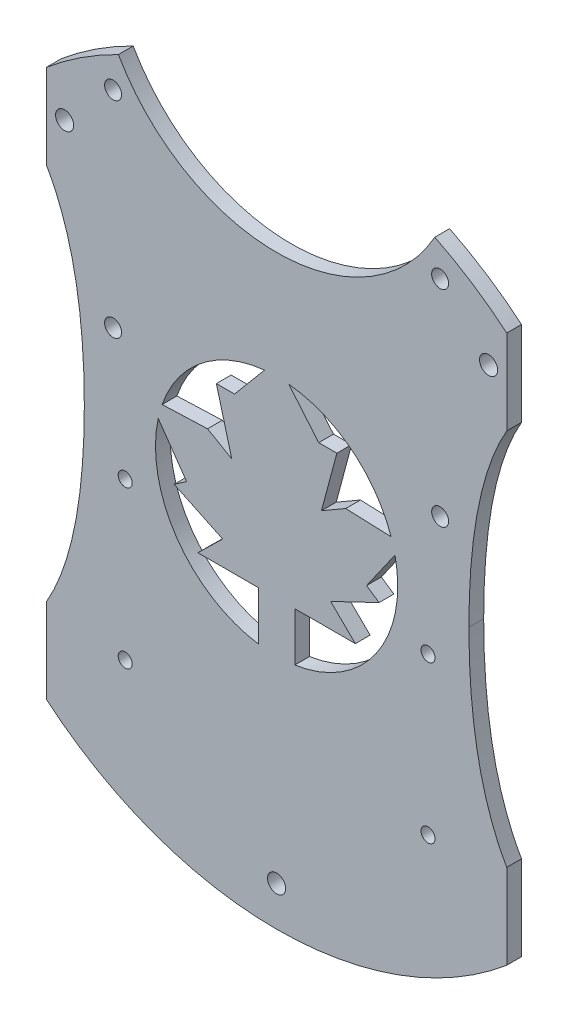
SolidWorks part; units mm, degrees
ref_plane "Front Plane" through (0, 0, 0) normal (0, 0, 1) x (1, 0, 0)
ref_plane "Top Plane" through (0, 0, 0) normal (0, 1, 0) x (1, 0, 0)
ref_plane "Right Plane" through (0, 0, 0) normal (1, 0, 0) x (0, 0, -1)
sketch "Sketch1" plane through (0, 0, 0) normal (0, 0, 1) x (1, 0, 0)
  line L0 (0, 47.9049) -> (0, -75) construction
  line L1 (-48.26, 57.4106) -> (-48.26, -57.4106)
  line L2 (48.26, 57.4106) -> (48.26, -57.4106)
  arc A0 (-33.1727, 67.265) -> (-48.26, 57.4106) centre (0, 0) ccw
  arc A1 (-33.1727, 67.265) -> (33.1727, 67.265) centre (0, 86.0049) ccw
  circle A2 centre (0, -66.675) radius 1.8987
  circle A3 centre (-44.45, 49.6966) radius 1.8987
  circle A4 centre (44.45, 49.6966) radius 1.8986
  arc A5 (-48.26, -57.4106) -> (48.26, -57.4106) centre (0, 0) ccw
  arc A6 (48.26, 57.4106) -> (33.1727, 67.265) centre (0, 0) ccw
  circle A7 centre (0, 0) radius 66.675 construction
  dimension "D8" = 3.7973
  dimension "D11" = 3.7973
  dimension "D5" = 150
  dimension "D7" = 133.35
  dimension "D2" = 66.3453
  dimension "D3" = 38.1
  dimension "D4" = 44.45
  dimension "D6" = 48.26
extrude "Boss-Extrude3" add sketch "Sketch1" along normal blind 3.0988
sketch "Sketch2" plane through (0, 0, 3.0988) normal (0, 0, 1) x (1, 0, 0)
  line L0 (0, 47.9049) -> (0, -75) construction
  line L1 (-34.925, -41.98) -> (34.925, -41.98) construction
  line L2 (-34.925, -61.03) -> (-34.925, -22.93) construction
  line L3 (-34.925, -61.03) -> (34.925, -61.03) construction
  line L4 (34.925, -61.03) -> (34.925, -22.93) construction
  line L5 (-34.925, -22.93) -> (34.925, -22.93) construction
  line L6 (0, -61.03) -> (0, -22.93) construction
  line L7 (-28.575, -55.7849) -> (-28.575, -28.1751) construction
  line L8 (-28.575, -55.7849) -> (28.575, -55.7849) construction
  line L9 (28.575, -55.7849) -> (28.575, -28.1751) construction
  line L10 (-28.575, -28.1751) -> (28.575, -28.1751) construction
  line L11 (-28.575, -55.7849) -> (28.575, -28.1751) construction
  line L12 (28.575, -55.7849) -> (-28.575, -28.1751) construction
  line L13 (-34.925, -9.1251) -> (34.925, -9.1251) construction
  line L14 (34.925, 9.9249) -> (34.925, -22.93) construction
  line L15 (-34.925, -22.93) -> (34.925, -22.93) construction
  line L16 (-34.925, 9.9249) -> (-34.925, -22.93) construction
  line L17 (-34.925, 9.9249) -> (34.925, 9.9249) construction
  line L18 (0, -22.93) -> (0, 9.9249) construction
  line L19 (-28.575, -22.93) -> (-28.575, 4.6798) construction
  line L20 (-28.575, -22.93) -> (28.575, -22.93) construction
  line L21 (28.575, -22.93) -> (28.575, 4.6798) construction
  line L22 (-28.575, 4.6798) -> (28.575, 4.6798) construction
  line L23 (-28.575, -22.93) -> (28.575, 4.6798) construction
  line L24 (28.575, -22.93) -> (-28.575, 4.6798) construction
  arc A0 (-33.1727, 67.265) -> (33.1727, 67.265) centre (0, 86.0049) ccw construction
  arc A1 (-48.26, -57.4106) -> (48.26, -57.4106) centre (0, 0) ccw construction
  circle A2 centre (-31.75, -41.98) radius 1.4732
  circle A3 centre (31.75, -41.98) radius 1.4732
  circle A4 centre (-31.75, -9.1251) radius 1.4732
  circle A5 centre (31.75, -9.1251) radius 1.4732
  point P8 (0, -41.98)
  point P25 (0, -9.1251)
  dimension "D7" = 2.9464
  dimension "D11" = 2.9464
  dimension "D1" = 57.15
  dimension "D2" = 27.6098
  dimension "D3" = 3.175
  dimension "D4" = 33.02
  dimension "D5" = 38.1
  dimension "D6" = 69.85
  dimension "D8" = 57.15
  dimension "D9" = 27.6098
  dimension "D10" = 32.8549
  dimension "D12" = 32.8549
  dimension "D13" = 69.85
  dimension "D14" = 28.575
extrude "Cut-Extrude1" cut sketch "Sketch2" against normal up to surface (3.0988 mm away) up to face at (1.8987, -66.675, 0)
sketch "Sketch3" plane through (0, 0, 3.0988) normal (0, 0, 1) x (1, 0, 0)
  line L0 (0, 47.9049) -> (0, -75) construction
  line L1 (0, 25.4) -> (0, -25.4) construction
  line L2 (8.8271, 17.78) -> (2.54, 25.2727)
  line L3 (8.8271, 17.78) -> (12.6371, 17.78)
  line L4 (12.6371, 17.78) -> (9.4043, 5.715)
  line L5 (9.4043, 5.715) -> (14.4843, 8.6479)
  line L6 (14.4843, 8.6479) -> (24.0093, 8.2894)
  line L7 (18.8681, -3.1406) -> (24.8262, 5.3684)
  line L8 (18.8681, -3.1406) -> (21.4871, -4.9356)
  line L9 (21.4871, -4.9356) -> (11.3271, -9.7979)
  line L10 (11.3271, -9.7979) -> (16.51, -14.8779)
  line L11 (16.51, -14.8779) -> (3.81, -14.8779)
  line L12 (3.81, -14.8779) -> (3.81, -25.1126)
  line L13 (-3.81, -14.8779) -> (-3.81, -25.1126)
  line L14 (-16.51, -14.8779) -> (-3.81, -14.8779)
  line L15 (-11.3271, -9.7979) -> (-16.51, -14.8779)
  line L16 (-21.4871, -4.9356) -> (-11.3271, -9.7979)
  line L17 (-18.8681, -3.1406) -> (-21.4871, -4.9356)
  line L18 (-18.8681, -3.1406) -> (-24.8262, 5.3684)
  line L19 (-14.4843, 8.6479) -> (-24.0093, 8.2894)
  line L20 (-9.4043, 5.715) -> (-14.4843, 8.6479)
  line L21 (-12.6371, 17.78) -> (-9.4043, 5.715)
  line L22 (-8.8271, 17.78) -> (-12.6371, 17.78)
  line L23 (-8.8271, 17.78) -> (-2.54, 25.2727)
  arc A0 (-33.1727, 67.265) -> (33.1727, 67.265) centre (0, 86.0049) ccw construction
  arc A1 (-48.26, -57.4106) -> (48.26, -57.4106) centre (0, 0) ccw construction
  arc A2 (3.81, -25.1126) -> (24.8262, 5.3684) centre (0, 0) ccw
  arc A3 (-24.8262, 5.3684) -> (-3.81, -25.1126) centre (0, 0) ccw
  arc A4 (-2.54, 25.2727) -> (-24.0093, 8.2894) centre (0, 0) ccw
  arc A5 (24.0093, 8.2894) -> (2.54, 25.2727) centre (0, 0) ccw
  circle A6 centre (0, 0) radius 25.4 construction
  dimension "D1" = 7.62
  dimension "D2" = 3.81
  dimension "D3" = 12.065
  dimension "D4" = 75
  dimension "D5" = 5.08
  dimension "D6" = 45
  dimension "D7" = 9.525
  dimension "D8" = 3.175
  dimension "D9" = 10.16
  dimension "D10" = 60
  dimension "D11" = 5.08
  dimension "D12" = 12.7
  dimension "D13" = 70
  dimension "D14" = 3.81
  dimension "D15" = 2.921
  dimension "D16" = 35
  dimension "D17" = 40
extrude "Cut-Extrude2" cut sketch "Sketch3" against normal up to surface (3.0988 mm away) up to face at (33.2232, -9.1251, 0)
sketch "Sketch4" plane through (0, 0, 3.0988) normal (0, 0, 1) x (1, 0, 0)
  line L0 (0, 47.9049) -> (0, -75) construction
  line L1 (-38.1, 64.09) -> (38.1, 64.09) construction
  line L2 (-38.1, 64.09) -> (-38.1, 13.29) construction
  line L3 (-38.1, 13.29) -> (38.1, 13.29) construction
  line L4 (38.1, 64.09) -> (38.1, 13.29) construction
  line L5 (0, 64.09) -> (0, 13.29) construction
  line L6 (-38.1, 38.69) -> (38.1, 38.69) construction
  arc A0 (-33.1727, 67.265) -> (33.1727, 67.265) centre (0, 86.0049) ccw construction
  arc A1 (-48.26, -57.4106) -> (48.26, -57.4106) centre (0, 0) ccw construction
  circle A2 centre (-34.29, 60.28) radius 1.778
  circle A3 centre (34.29, 60.28) radius 1.778
  circle A4 centre (34.29, 17.1) radius 1.778
  circle A5 centre (-34.29, 17.1) radius 1.778
  dimension "D3" = 3.556
  dimension "D5" = 3.81
  dimension "D6" = 3.81
  dimension "D1" = 76.2
  dimension "D2" = 50.8
  dimension "D4" = 28.575
extrude "Cut-Extrude3" cut sketch "Sketch4" against normal up to surface (3.0988 mm away) up to face at (-12.3976, 14.4374, 0)
sketch "Sketch5" plane through (0, 0, 3.0988) normal (0, 0, 1) x (1, 0, 0)
  line L0 (0, 47.9049) -> (0, -75) construction
  line L1 (48.26, 39.6306) -> (48.26, -39.6306)
  line L2 (-48.26, 39.6306) -> (-48.26, -39.6306)
  line L3 (-48.26, 57.4106) -> (-48.26, -57.4106) construction
  line L4 (-48.26, 0) -> (48.26, 0) construction
  line L5 (48.26, -57.4106) -> (48.26, 57.4106) construction
  line L6 (-32.6036, 12.513) -> (-64.3536, 67.5056) construction
  arc A0 (-33.1727, 67.265) -> (33.1727, 67.265) centre (0, 86.0049) ccw construction
  arc A1 (-48.26, -57.4106) -> (48.26, -57.4106) centre (0, 0) ccw construction
  spline S0 degree 2 poles (-48.26, 39.6306) (-40.3225, 25.8824) (-40.3225, 0) knots 0 0 0 1 1 1
  spline S1 degree 2 poles (-48.26, -39.6306) (-40.3225, -25.8824) (-40.3225, 0) knots 0 0 0 1 1 1
  spline S2 degree 2 poles (48.26, -39.6306) (40.3225, -25.8824) (40.3225, 0) knots 0 0 0 1 1 1
  spline S3 degree 2 poles (48.26, 39.6306) (40.3225, 25.8824) (40.3225, 0) knots 0 0 0 1 1 1
  dimension "D2" = 31.75
  dimension "D1" = 17.78
  dimension "D3" = 30
extrude "Cut-Extrude4" cut sketch "Sketch5" against normal up to surface (3.0988 mm away) up to face at (-32.512, 17.1, 0)
